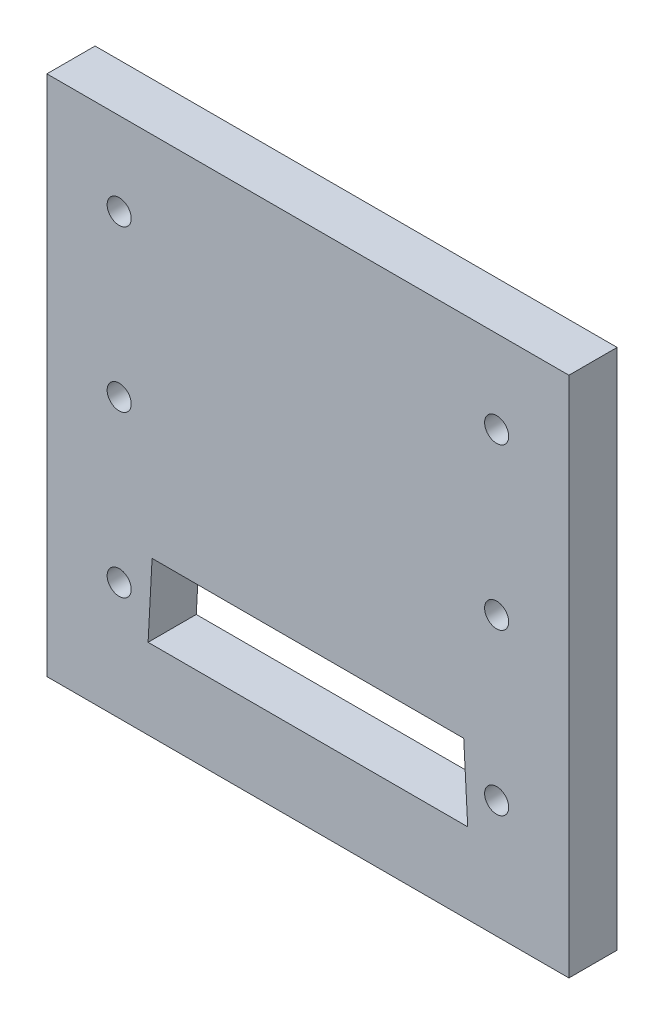
SolidWorks part; units mm, degrees
ref_plane "Front Plane" through (0, 0, 0) normal (0, 0, 1) x (1, 0, 0)
ref_plane "Top Plane" through (0, 0, 0) normal (0, 1, 0) x (1, 0, 0)
ref_plane "Right Plane" through (0, 0, 0) normal (1, 0, 0) x (0, 0, -1)
sketch "Sketch1" plane through (0, 0, 0) normal (0, 0, 1) x (1, 0, 0)
  line L0 (19.9, 0) -> (19.9, 20.7114) construction
  line L1 (0, 0) -> (39.8, 0)
  line L2 (0, 0) -> (0.5, 9.3)
  line L3 (0.5, 9.3) -> (39.3, 9.3)
  line L4 (39.8, 0) -> (39.3, 9.3)
  line L5 (-3.6, 4.65) -> (43.4, 4.65) construction
  line L6 (-12.6, 55) -> (52.4, 55)
  line L7 (-12.6, 55) -> (-12.6, -10)
  line L8 (-12.6, -10) -> (52.4, -10)
  line L9 (52.4, 55) -> (52.4, -10)
  circle A0 centre (-3.6, 4.65) radius 1.5
  circle A1 centre (43.4, 4.65) radius 1.5
  circle A2 centre (-3.6, 24.65) radius 1.5
  circle A3 centre (43.4, 24.65) radius 1.5
  circle A4 centre (-3.6, 44.65) radius 1.5
  circle A5 centre (43.4, 44.65) radius 1.5
  point P7 (19.9, 9.3)
  point P16 (19.9, 4.65)
  point P17 (19.9, 55)
  point P28 (-2.3585, 34.8779)
  dimension "D4" = 3
  dimension "D7" = 4.65
  dimension "D1" = 38.8
  dimension "D2" = 39.8
  dimension "D3" = 9.3
  dimension "D5" = 65
  dimension "D6" = 47
  dimension "D8" = 65
  dimension "D9" = 3
  dimension "D10" = 20
  dimension "D11" = 23.5
  dimension "D12" = 10
extrude "Boss-Extrude1" add sketch "Sketch1" along normal blind 6
